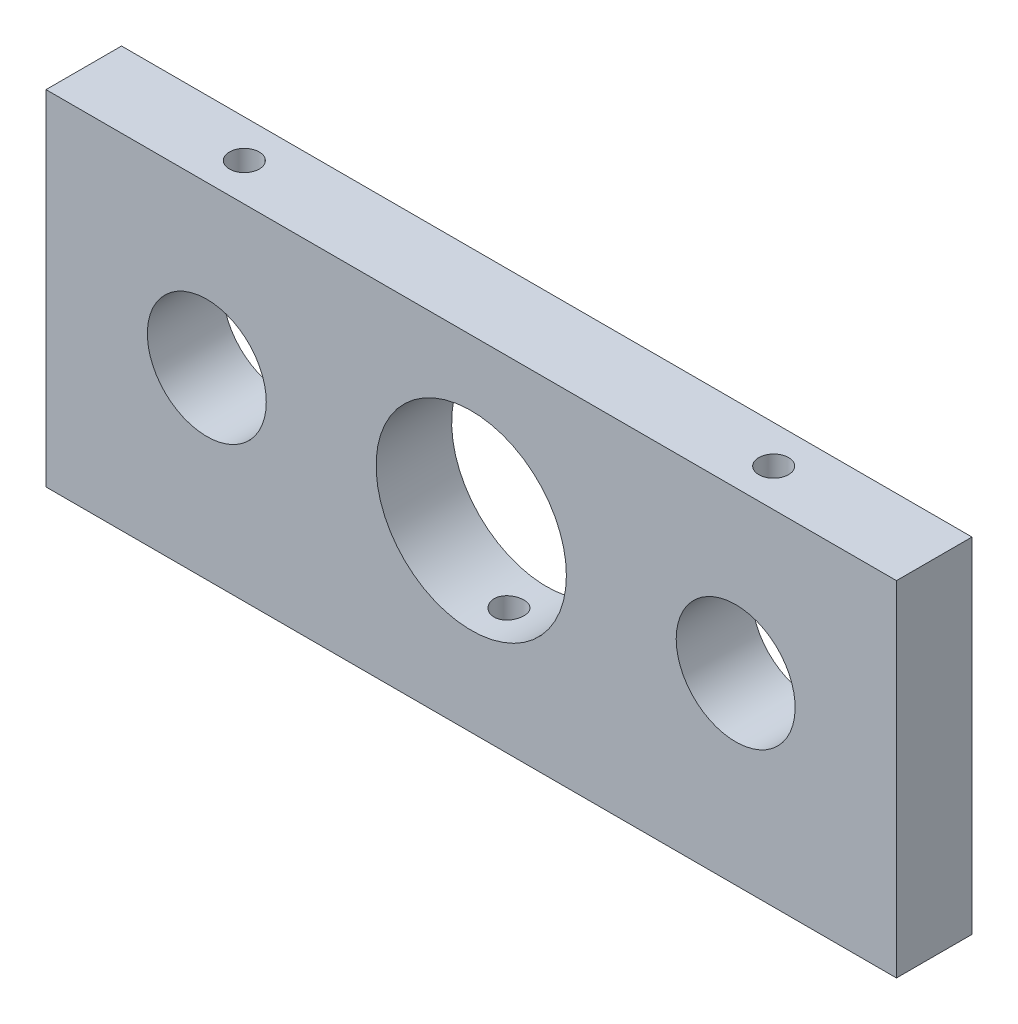
SolidWorks part; units mm, degrees
ref_plane "Plano frontal" through (0, 0, 0) normal (0, 0, 1) x (1, 0, 0)
ref_plane "Plano superior" through (0, 0, 0) normal (0, 1, 0) x (1, 0, 0)
ref_plane "Plano direito" through (0, 0, 0) normal (1, 0, 0) x (0, 0, -1)
sketch "Esboço1" plane through (0, 0, 0) normal (0, 0, 1) x (1, 0, 0)
  line L0 (71.505, 27) -> (-71.505, -27) construction
  line L1 (-71.505, 27) -> (71.505, 27)
  line L2 (-71.505, 27) -> (-71.505, -27)
  line L3 (-71.505, -27) -> (71.505, -27)
  line L4 (71.505, 27) -> (71.505, -27)
  dimension "D1" = 143.01
  dimension "D2" = 54
extrude "Ressalto-extrusão1" add sketch "Esboço1" along normal blind 10
sketch "Esboço14" plane through (-71.505, 0, 0) normal (-1, 0, 0) x (0, 0, 1)
  line L1 (0, 27) -> (-2.7, 27)
  line L2 (0, 27) -> (0, -30.87)
  line L3 (0, -30.87) -> (-2.7, -30.87)
  line L4 (-2.7, 27) -> (-2.7, -30.87)
  dimension "D1" = 2.7
extrude "Ressalto-extrusão3" add sketch "Esboço14" against normal up to surface (143.01 mm away) up to face at (71.505, 0, 5)
sketch "Esboço2" plane through (0, 0, 10) normal (0, 0, 1) x (1, 0, 0)
  circle A0 centre (0, 0) radius 16
  dimension "D1" = 32
extrude "Circulo rolamento" cut sketch "Esboço2" against normal blind 19
sketch "Esboço7" plane through (0, 0, 10) normal (0, 0, 1) x (1, 0, 0)
  line L0 (-71.505, 27) -> (-71.505, -27) construction
  line L1 (0, 20.0417) -> (0, -20.5817) construction
  circle A0 centre (-44.465, 0) radius 10
  circle A1 centre (44.465, 0) radius 10
  dimension "D2" = 20
  dimension "D3" = 27.04
  dimension "D5" = 27
extrude "Corte-extrusão3" cut sketch "Esboço7" against normal blind 19
sketch "Esboço8" plane through (0, 0, 10) normal (0, 0, 1) x (1, 0, 0)
  line L1 (-71.505, -27) -> (71.505, -27)
  line L2 (-71.505, -27) -> (-71.505, -30.87)
  line L3 (-71.505, -30.87) -> (71.505, -30.87)
  line L4 (71.505, -27) -> (71.505, -30.87)
  dimension "D1" = 143.01
  dimension "D2" = 3.87
extrude "Ressalto-extrusão2" add sketch "Esboço8" against normal blind 10
sketch "Esboço12" plane through (0, -30.87, 0) normal (0, -1, 0) x (1, 0, 0)
  line L0 (-71.505, 3.65) -> (71.505, 3.65) construction
  line L1 (-71.505, -2.7) -> (-71.505, 10) construction
  line L2 (71.505, -2.7) -> (71.505, 10) construction
  line L3 (0, 3.65) -> (0, -2.7) construction
  line L4 (71.505, -2.7) -> (-71.505, -2.7) construction
  circle A0 centre (-61.505, 3.65) radius 2.5
  circle A1 centre (61.505, 3.65) radius 2.5
  circle A2 centre (0, 3.65) radius 2.5
  circle A3 centre (-33.505, 3.65) radius 2.5
  circle A4 centre (33.505, 3.65) radius 2.5
  dimension "D1" = 5
  dimension "D2" = 5
  dimension "D7" = 5
  dimension "D4" = 10
  dimension "D9" = 38
extrude "Corte-extrusão6" cut sketch "Esboço12" against normal blind 17
sketch "Esboço15" plane through (0, 27, 0) normal (0, 1, 0) x (1, 0, 0)
  line L0 (71.505, -3.65) -> (-71.505, -3.65) construction
  line L1 (71.505, -10) -> (71.505, 2.7) construction
  line L2 (-71.505, -10) -> (-71.505, 2.7) construction
  circle A0 centre (-44.505, -3.65) radius 2.5
  circle A1 centre (44.505, -3.65) radius 2.5
  dimension "D3" = 5
  dimension "D4" = 5
  dimension "D1" = 27
  dimension "D2" = 27
extrude "Corte-extrusão7" cut sketch "Esboço15" against normal up to next
